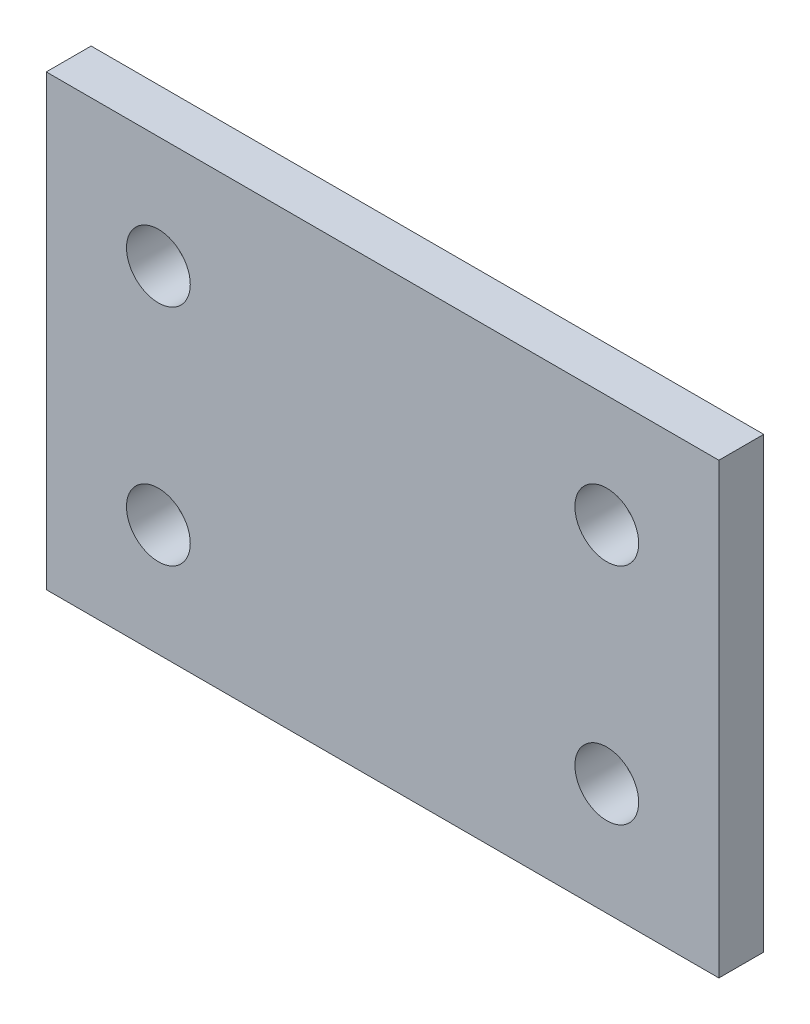
SolidWorks part; units mm, degrees
ref_plane "Front Plane" through (0, 0, 0) normal (0, 0, 1) x (1, 0, 0)
ref_plane "Top Plane" through (0, 0, 0) normal (0, 1, 0) x (1, 0, 0)
ref_plane "Right Plane" through (0, 0, 0) normal (1, 0, 0) x (0, 0, -1)
sketch "Sketch1" plane through (0, 0, 0) normal (0, 0, 1) x (1, 0, 0)
  line L1 (-15, -10) -> (15, -10)
  line L2 (-15, -10) -> (-15, 10)
  line L3 (-15, 10) -> (15, 10)
  line L4 (15, -10) -> (15, 10)
  line L5 (-15, -10) -> (15, 10) construction
  line L6 (-15, 10) -> (15, -10) construction
  point P0 (0, 0)
  dimension "D1" = 30
  dimension "D2" = 20
extrude "Boss-Extrude1" add sketch "Sketch1" along normal blind 2
sketch "Sketch2" plane through (0, 0, 2) normal (0, 0, 1) x (1, 0, 0)
  line L0 (15, 10) -> (-15, 10) construction
  line L3 (15, -10) -> (15, 10) construction
  line L4 (10, 5) -> (-10, 5) construction
  circle A4 centre (10, 5) radius 1.4224
  circle A5 centre (-10, 5) radius 1.4224
  circle A6 centre (-10, -5) radius 1.4224
  circle A7 centre (10, -5) radius 1.4224
  point P0 (0, 0)
  dimension "D6" = 2.8448
  dimension "D7" = 5
  dimension "D8" = 5
  dimension "D11" = 20
  dimension "D9" = 2
  dimension "D10" = 2
extrude "Cut-Extrude1" cut sketch "Sketch2" against normal up to next
